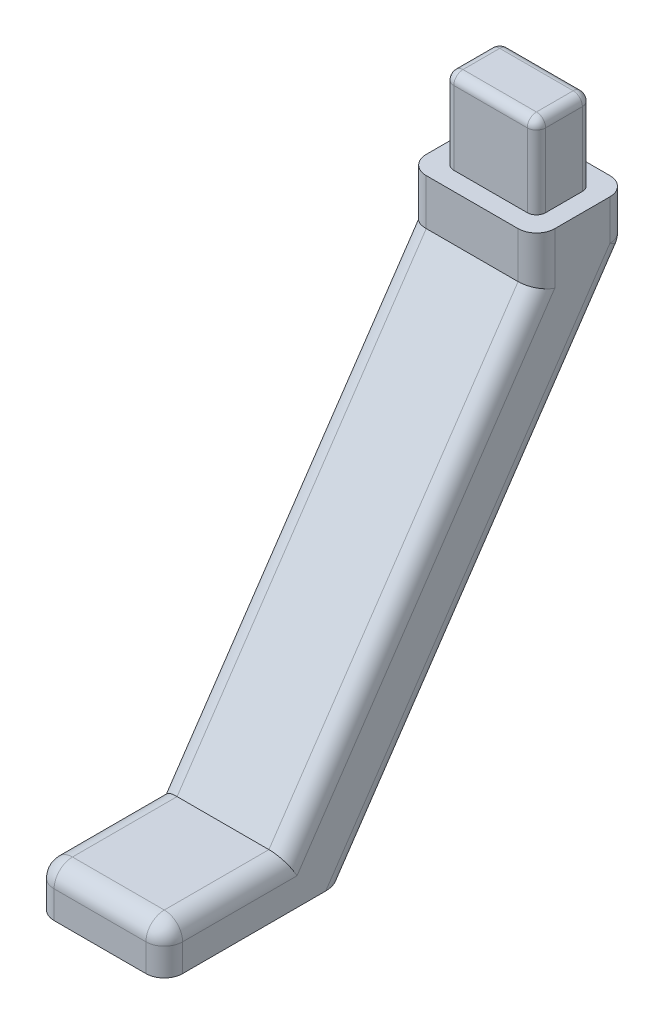
SolidWorks part; units mm, degrees
ref_plane "Front Plane" through (0, 0, 0) normal (0, 0, 1) x (1, 0, 0)
ref_plane "Top Plane" through (0, 0, 0) normal (0, 1, 0) x (1, 0, 0)
ref_plane "Right Plane" through (0, 0, 0) normal (1, 0, 0) x (0, 0, -1)
sketch "Sketch1" plane through (0, 0, 0) normal (0, 1, 0) x (1, 0, 0)
  line L1 (-5, 3) -> (5, 3)
  line L2 (-5, 3) -> (-5, -3)
  line L3 (-5, -3) -> (5, -3)
  line L4 (5, 3) -> (5, -3)
  line L5 (-5, 3) -> (5, -3) construction
  line L6 (-5, -3) -> (5, 3) construction
  point P0 (0, 0)
  dimension "D1" = 10
  dimension "D2" = 6
extrude "Boss-Extrude1" add sketch "Sketch1" along normal blind 9
sketch "Sketch2" plane through (0, 0, 0) normal (0, -1, 0) x (1, 0, 0)
  line L1 (-7, 5) -> (7, 5)
  line L2 (-7, 5) -> (-7, -5)
  line L3 (-7, -5) -> (7, -5)
  line L4 (7, 5) -> (7, -5)
  line L5 (-7, 5) -> (7, -5) construction
  line L6 (-7, -5) -> (7, 5) construction
  point P0 (0, 0)
  dimension "D1" = 14
  dimension "D2" = 10
extrude "Boss-Extrude2" add sketch "Sketch2" along normal blind 5
sketch "Sketch4" plane through (0, 0, 0) normal (1, 0, 0) x (0, 0, -1)
  line L0 (-5, -5) -> (-32.1355, -45)
  line L2 (-32.1355, -45) -> (-45.5274, -45)
  line L3 (-45.5274, -45) -> (-45.5274, -50)
  line L4 (-45.5274, -50) -> (-25.5274, -50)
  line L5 (-25.5274, -50) -> (5, -5)
  line L6 (-3, 0) -> (3, 0) construction
  line L11 (5, 0) -> (-5, 0)
  line L12 (-5, 0) -> (-5, -5)
  line L13 (-5, -5) -> (5, -5)
  line L14 (5, -5) -> (5, 0)
  line L17 (-5, -5) -> (5, -5)
  dimension "D1" = 20
  dimension "D2" = 0
  dimension "D3" = 50
  dimension "D4" = 5
extrude "Boss-Extrude3" add sketch "Sketch4" along normal mid plane 14
fillet "Fillet1" radius 2 14 edges at (-7, -27.5, 10.2637) (7, -27.5, 10.2637) (7, -2.5, -5) (-7, -2.5, -5) (-7, -2.5, 5) (0, -5, -5) (-7, -25, 18.5677) (7, -25, 18.5677) (7, -2.5, 5) (-7, -47.5, 45.5274) (7, -47.5, 45.5274) (-7, -45, 38.8314) (7, -45, 38.8314) (0, -45, 45.5274)
fillet "Fillet2" radius 1 8 edges at (0, 9, -3) (-5, 9, 0) (-5, 4.5, -3) (-5, 4.5, 3) (0, 9, 3) (5, 9, 0) (5, 4.5, -3) (5, 4.5, 3)
